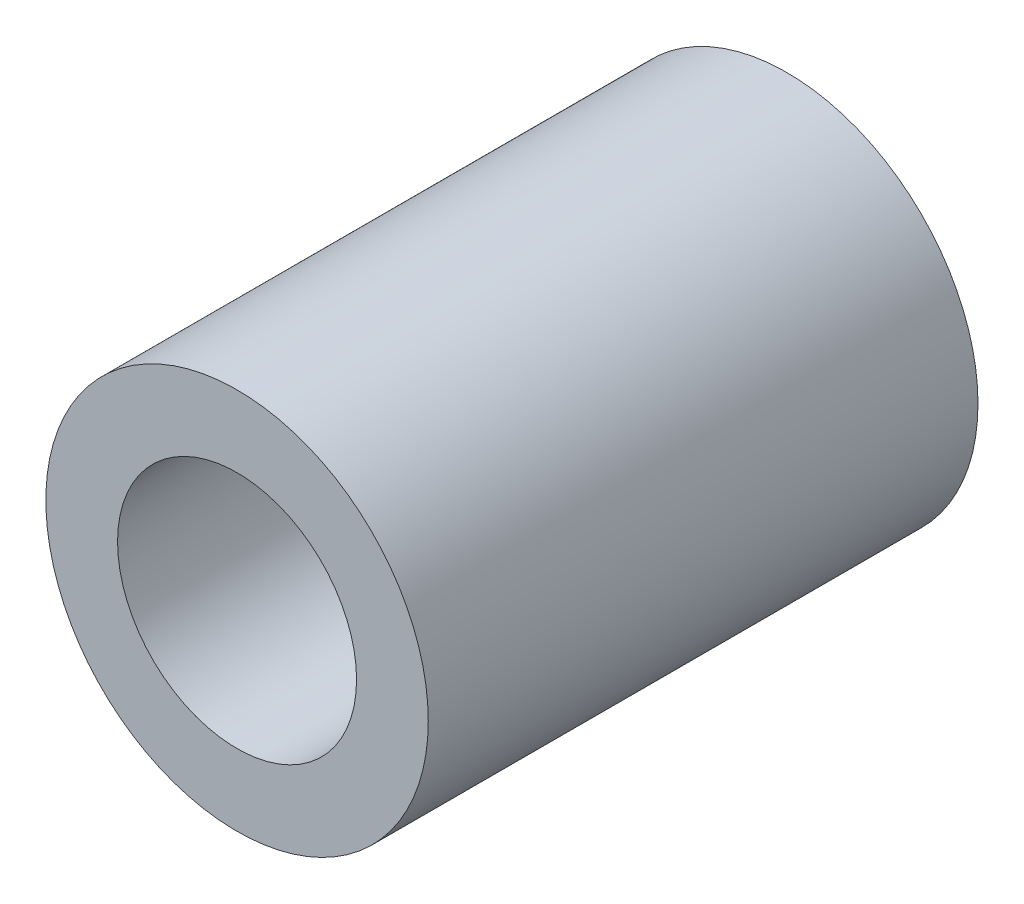
SolidWorks part; units mm, degrees
ref_plane "Ebene vorne" through (0, 0, 0) normal (0, 0, 1) x (1, 0, 0)
ref_plane "Ebene oben" through (0, 0, 0) normal (0, 1, 0) x (1, 0, 0)
ref_plane "Ebene rechts" through (0, 0, 0) normal (1, 0, 0) x (0, 0, -1)
sketch "Skizze1" plane through (0, 0, 0) normal (0, 0, 1) x (1, 0, 0)
  circle A0 centre (0, 0) radius 2.5
  circle A1 centre (0, 0) radius 8
  dimension "D1" = 5
  dimension "D2" = 16
extrude "Aufsatz-Linear austragen1" add sketch "Skizze1" along normal blind 23
sketch "Skizze2" plane through (0, 0, 23) normal (0, 0, 1) x (1, 0, 0)
  circle A0 centre (0, 0) radius 5
  dimension "D1" = 10
extrude "Schnitt-Linear austragen1" cut sketch "Skizze2" against normal blind 11.5
